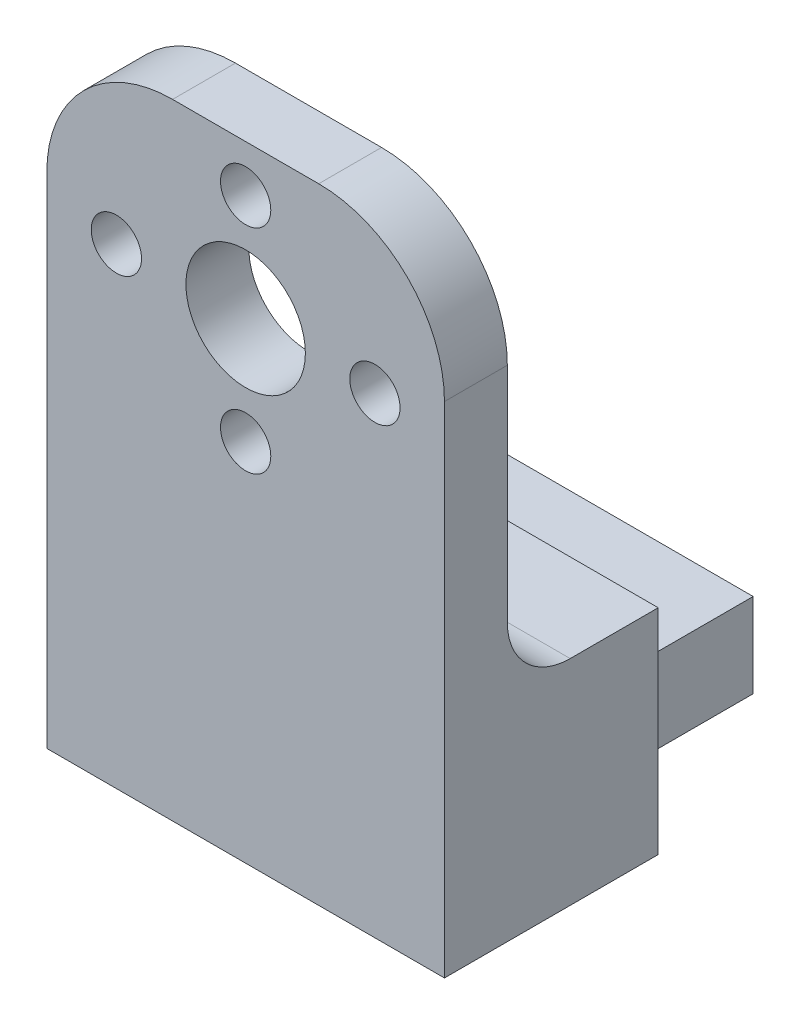
SolidWorks part; units mm, degrees
ref_plane "Front Plane" through (0, 0, 0) normal (0, 0, 1) x (1, 0, 0)
ref_plane "Top Plane" through (0, 0, 0) normal (0, 1, 0) x (1, 0, 0)
ref_plane "Right Plane" through (0, 0, 0) normal (1, 0, 0) x (0, 0, -1)
sketch "Sketch1" plane through (0, 0, 0) normal (0, 1, 0) x (1, 0, 0)
  line L1 (15.81, 8.5) -> (-15.81, 8.5)
  line L2 (15.81, 8.5) -> (15.81, -8.5)
  line L3 (15.81, -8.5) -> (-15.81, -8.5)
  line L4 (-15.81, 8.5) -> (-15.81, -8.5)
  line L5 (15.81, 8.5) -> (-15.81, -8.5) construction
  line L6 (15.81, -8.5) -> (-15.81, 8.5) construction
  point P0 (0, 0)
  dimension "D1" = 31.62
extrude "Boss-Extrude1" add sketch "Sketch1" along normal blind 17
sketch "Sketch2" plane through (0, 0, -8.5) normal (0, 0, -1) x (-1, 0, 0)
  line L0 (-15.81, 0) -> (15.81, 0) construction
  line L1 (-13.66, 11.85) -> (13.66, 11.85)
  line L2 (-13.66, 11.85) -> (-13.66, 5.15)
  line L3 (-13.66, 5.15) -> (13.66, 5.15)
  line L4 (13.66, 11.85) -> (13.66, 5.15)
  line L5 (-13.66, 11.85) -> (13.66, 5.15) construction
  line L6 (-13.66, 5.15) -> (13.66, 11.85) construction
  line L7 (0, 11.85) -> (0, 17)
  line L8 (-15.81, 17) -> (15.81, 17) construction
  line L9 (0, 5.15) -> (0, 0)
  point P0 (0, 8.5)
  point P7 (0, 0)
extrude "Boss-Extrude2" add sketch "Sketch2" along normal blind 9.7 contours L4 L1 L2 L3
sketch "Sketch3" plane through (0, 17, 0) normal (0, 1, 0) x (1, 0, 0)
  line L1 (15.81, -3.5) -> (-15.81, -3.5)
  line L2 (15.81, -3.5) -> (15.81, -8.5)
  line L3 (15.81, -8.5) -> (-15.81, -8.5)
  line L4 (-15.81, -3.5) -> (-15.81, -8.5)
extrude "Boss-Extrude3" add sketch "Sketch3" along normal blind 32.7
sketch "Sketch4" plane through (0, 0, 8.5) normal (0, 0, 1) x (1, 0, 0)
  line L0 (0, 0) -> (0, 37.5)
  line L1 (-15.81, 0) -> (15.81, 0) construction
  line L2 (-4.75, 37.5) -> (-15.81, 37.5)
  line L5 (0, 42.25) -> (0, 49.7)
  line L7 (0, 37.5) -> (0, 25.3)
  line L8 (-15.81, 49.7) -> (-15.81, 0) construction
  line L9 (4.75, 37.5) -> (15.81, 37.5)
  line L10 (15.81, 49.7) -> (15.81, 0) construction
  line L11 (-15.81, 49.7) -> (15.81, 49.7) construction
  circle A0 centre (0, 37.5) radius 4.75
  circle A1 centre (-10.28, 37.5) radius 2
  circle A2 centre (10.28, 37.5) radius 2
  circle A3 centre (0, 45.975) radius 2
  circle A4 centre (0, 29.025) radius 2
  point P25 (0, 45.975)
extrude "Cut-Extrude1" cut sketch "Sketch4" against normal blind 5
fillet "Fillet1" radius 10 2 edges at (-15.81, 49.7, 6) (15.81, 49.7, 6)
fillet "Fillet2" radius 5 1 edges at (0, 17, 3.5)
